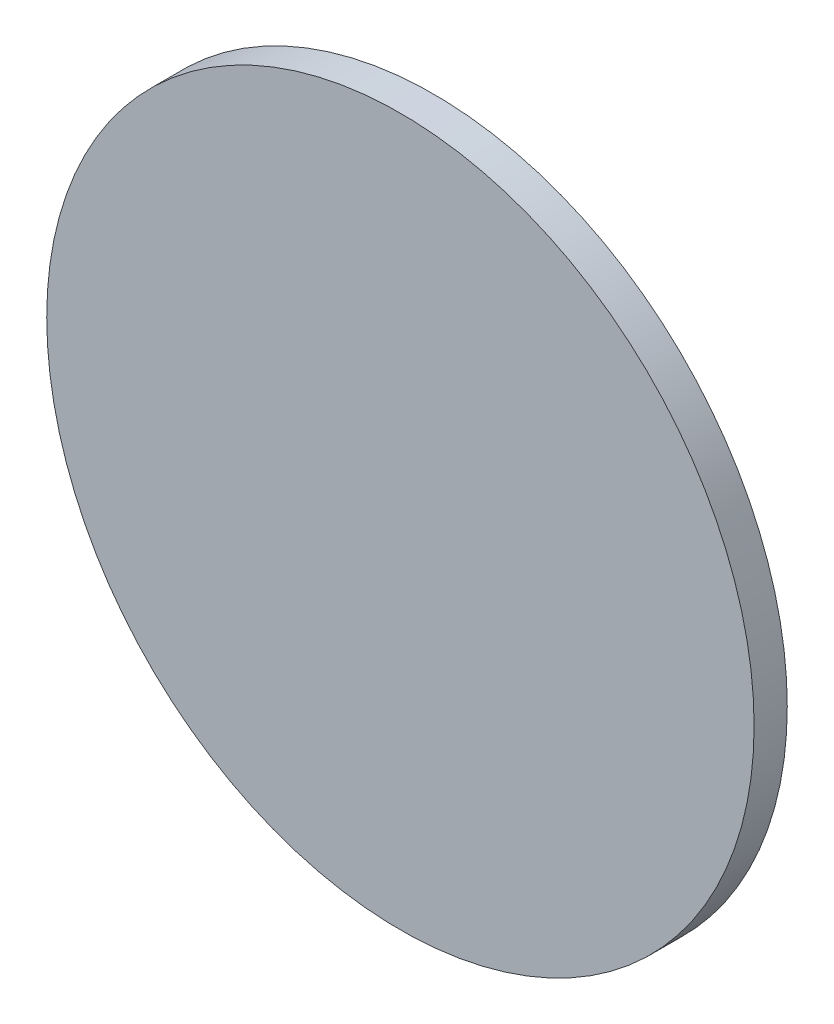
SolidWorks part; units mm, degrees
ref_plane "前视基准面" through (0, 0, 0) normal (0, 0, 1) x (1, 0, 0)
ref_plane "上视基准面" through (0, 0, 0) normal (0, 1, 0) x (1, 0, 0)
ref_plane "右视基准面" through (0, 0, 0) normal (1, 0, 0) x (0, 0, -1)
sketch "草图2" plane through (0, 0, 0) normal (0, 0, 1) x (1, 0, 0)
  circle A0 centre (0, 0) radius 16
  dimension "D1" = 32
extrude "凸台-拉伸1" add sketch "草图2" along normal blind 1.5
